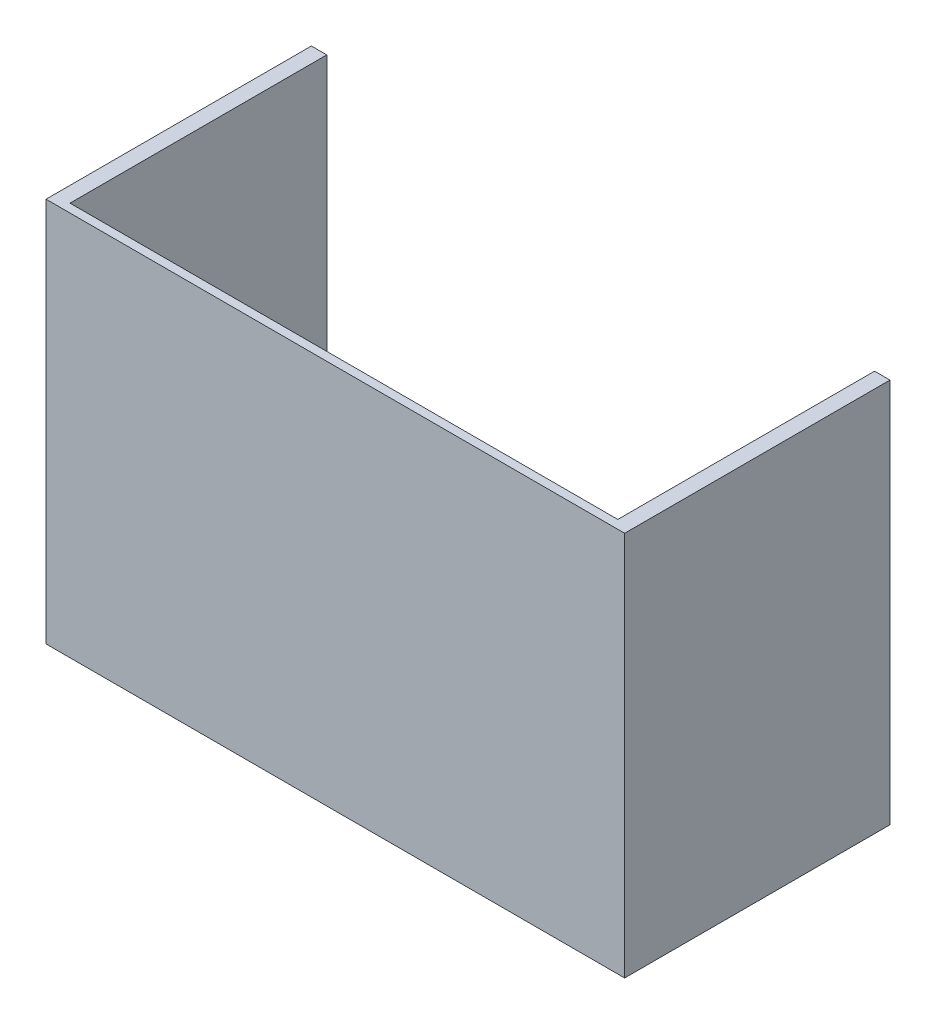
SolidWorks part; units mm, degrees
ref_plane "Front Plane" through (0, 0, 0) normal (0, 0, 1) x (1, 0, 0)
ref_plane "Top Plane" through (0, 0, 0) normal (0, 1, 0) x (1, 0, 0)
ref_plane "Right Plane" through (0, 0, 0) normal (1, 0, 0) x (0, 0, -1)
sketch "Sketch1" plane through (0, 155, 0) normal (0, -1, 0) x (1, 0, 0)
  line L0 (-261, 43) -> (-207, 43) construction
  line L1 (-195.2, 13) -> (-197, 13)
  line L2 (-195.2, 13) -> (-195.2, 44)
  line L3 (-195.2, 44) -> (-262.8, 44)
  line L4 (-262.8, 13) -> (-262.8, 44)
  line L6 (-197, 13) -> (-197, 43)
  line L7 (-197, 43) -> (-261, 43)
  line L8 (-261, 13) -> (-261, 43)
  line L9 (-261, 13) -> (-262.8, 13)
extrude "Boss-Extrude1" add sketch "Sketch1" along normal up to surface (45 mm away)
